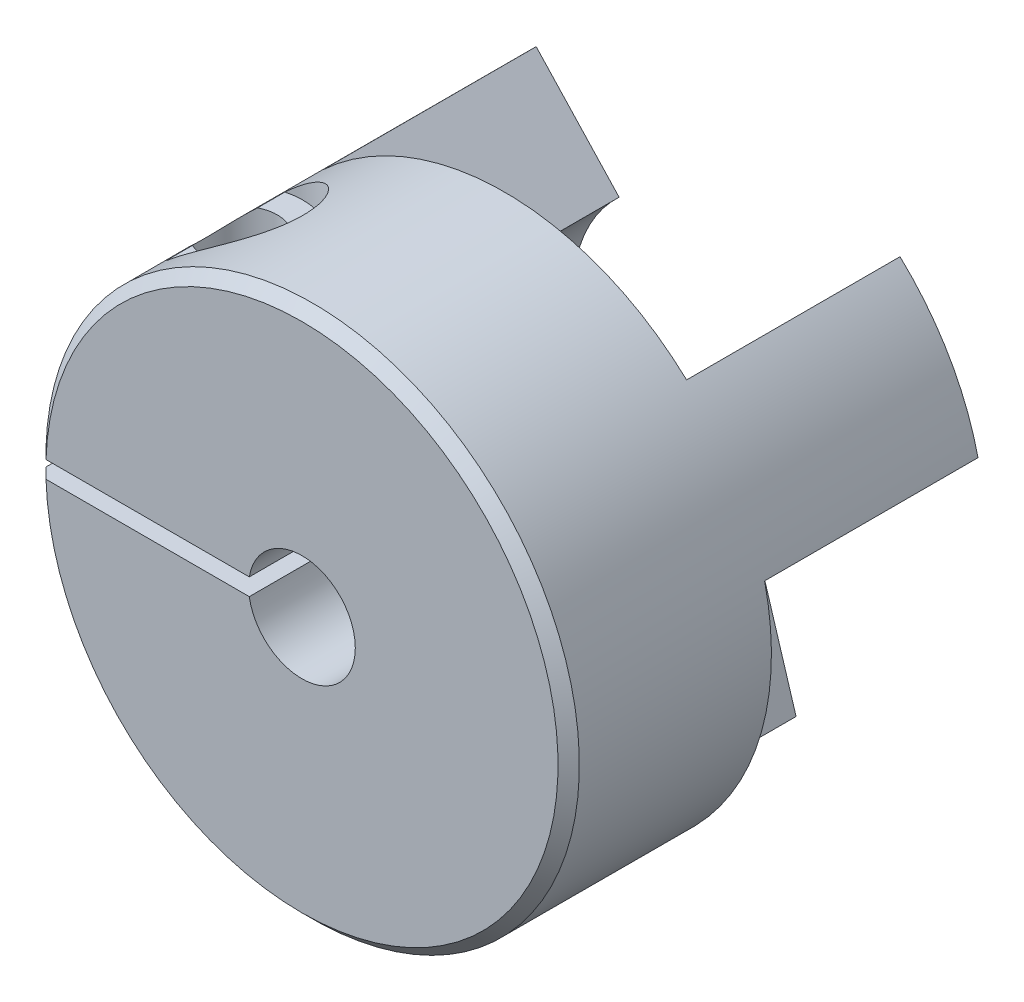
SolidWorks part; units mm, degrees
ref_plane "Front Plane" through (0, 0, 0) normal (0, 0, 1) x (1, 0, 0)
ref_plane "Top Plane" through (0, 0, 0) normal (0, 1, 0) x (1, 0, 0)
ref_plane "Right Plane" through (0, 0, 0) normal (1, 0, 0) x (0, 0, -1)
ref_plane "Plane1" through (0, 0, 0) normal (0, -1, 0) x (1, 0, 0)
sketch "Sketch1" plane through (0, 0, 0) normal (0, -1, 0) x (1, 0, 0)
  line L0 (12.5, 30) -> (0, 30)
  line L1 (0, 30) -> (0, 10.5)
  line L2 (0, 10.5) -> (12.5, 10.5)
  line L3 (12.5, 10.5) -> (12.5, 30)
  line L4 (0, 30) -> (0, 10.5) construction
revolve "Revolve1" add sketch "Sketch1" angle 360 about L4
sketch "Sketch2" plane through (0, 0, 10.5) normal (0, 0, -1) x (-1, 0, 0)
  line L0 (-3.6546, -11.9538) -> (-1.9881, -6.5029)
  line L1 (1.9881, -6.5029) -> (3.6546, -11.9538)
  arc A0 (-1.9881, -6.5029) -> (1.9881, -6.5029) centre (0, 0) ccw
  arc A1 (3.6546, -11.9538) -> (-3.6546, -11.9538) centre (0, 0) ccw
extrude "Cut-Extrude1" cut sketch "Sketch2" against normal blind 10
sketch "Sketch3" plane through (0, 0, 20.5) normal (0, 0, -1) x (-1, 0, 0)
  line L0 (-6.6257, 1.5297) -> (-12.1796, 2.8119)
  line L1 (-8.525, 9.1419) -> (-4.6376, 4.9732)
  arc A0 (-4.6376, 4.9732) -> (-6.6257, 1.5297) centre (0, 0) ccw
  arc A1 (-12.1796, 2.8119) -> (-8.525, 9.1419) centre (0, 0) cw
extrude "Boss-Extrude1" add sketch "Sketch3" along normal blind 10
sketch "Sketch4" plane through (0, 0, 20.5) normal (0, 0, -1) x (-1, 0, 0)
  line L0 (4.6376, 4.9732) -> (8.525, 9.1419)
  line L1 (12.1796, 2.8119) -> (6.6257, 1.5297)
  arc A0 (6.6257, 1.5297) -> (4.6376, 4.9732) centre (0, 0) ccw
  arc A1 (8.525, 9.1419) -> (12.1796, 2.8119) centre (0, 0) cw
extrude "Boss-Extrude2" add sketch "Sketch4" along normal blind 10
sketch "Sketch5" plane through (0, 0, 20.5) normal (0, 0, -1) x (-1, 0, 0)
  line L0 (12.4936, 0.4) -> (2.4678, 0.4)
  line L1 (2.4678, -0.4) -> (12.4936, -0.4)
  arc A0 (12.4936, -0.4) -> (12.4936, 0.4) centre (0, 0) ccw
  arc A1 (2.4678, 0.4) -> (2.4678, -0.4) centre (0, 0) cw
extrude "Cut-Extrude2" cut sketch "Sketch5" against normal through all
sketch "Sketch6" plane through (0, 0, 0) normal (0, -1, 0) x (1, 0, 0)
  line L0 (2.5, 30) -> (0, 30)
  line L1 (0, 30) -> (0, 20.5)
  line L2 (0, 20.5) -> (2.5, 20.5)
  line L3 (2.5, 20.5) -> (2.5, 30)
  line L4 (0, 30) -> (0, 20.5) construction
revolve "Cut-Revolve1" cut sketch "Sketch6" angle 360 about L4
ref_plane "Plane2" through (0, 11.5827, 0) normal (0, 1, 0) x (1, 0, 0)
hole_wizard "CBORE for M3 Hex Head Machine Screw1" positions "Sketch8" profile "Sketch7" counterbore size "M3" standard "ANSI Metric"
sketch "Sketch8" plane through (0, 11.5827, 0) normal (0, 1, 0) x (1, 0, 0)
  point P0 (-7.6, -25.25)
sketch "Sketch7" plane through (-7.6, 11.5827, 25.25) normal (1, 0, 0) x (0, 0, 1)
  line L0 (0, 0) -> (0, 11.1827)
  line L1 (0, 11.1827) -> (1.7, 11.1827)
  line L3 (1.7, 11.1827) -> (1.7, 2.2827)
  line L4 (1.7, 2.2827) -> (2.9, 2.2827)
  line L5 (2.9, 2.2827) -> (2.9, 0)
  line L7 (2.9, 0) -> (0, 0)
  line L11 (0, -6.35) -> (0, 107.95) construction
  dimension "Thru Hole Dia." = 3.4
  dimension "Thru Hole Depth" = 11.1827
  dimension "C'Bore Dia." = 5.8
  dimension "C'Bore Depth" = 2.2827
hole_wizard "Ø2.5 (2.5) Diameter Hole1" positions "Sketch10" profile "Sketch9" hole size "Ø2.5" standard "ANSI Metric"
sketch "Sketch10" plane through (0, -0.4, 0) normal (0, 1, 0) x (1, 0, 0)
  point P0 (-7.6, -25.25)
sketch "Sketch9" plane through (-7.6, -0.4, 25.25) normal (1, 0, 0) x (0, 0, 1)
  line L0 (0, 0) -> (0, 12.1)
  line L1 (0, 12.1) -> (1.25, 12.1)
  line L2 (1.25, 12.1) -> (1.25, 0)
  line L5 (1.25, 0) -> (0, 0)
  line L11 (0, -6.35) -> (0, 107.95) construction
  dimension "Thru Hole Dia." = 2.5
  dimension "Thru Hole Depth" = 12.1
chamfer "Chamfer1" distance 0.5 angle 45 1 edges at (12.5, 0, 30)
